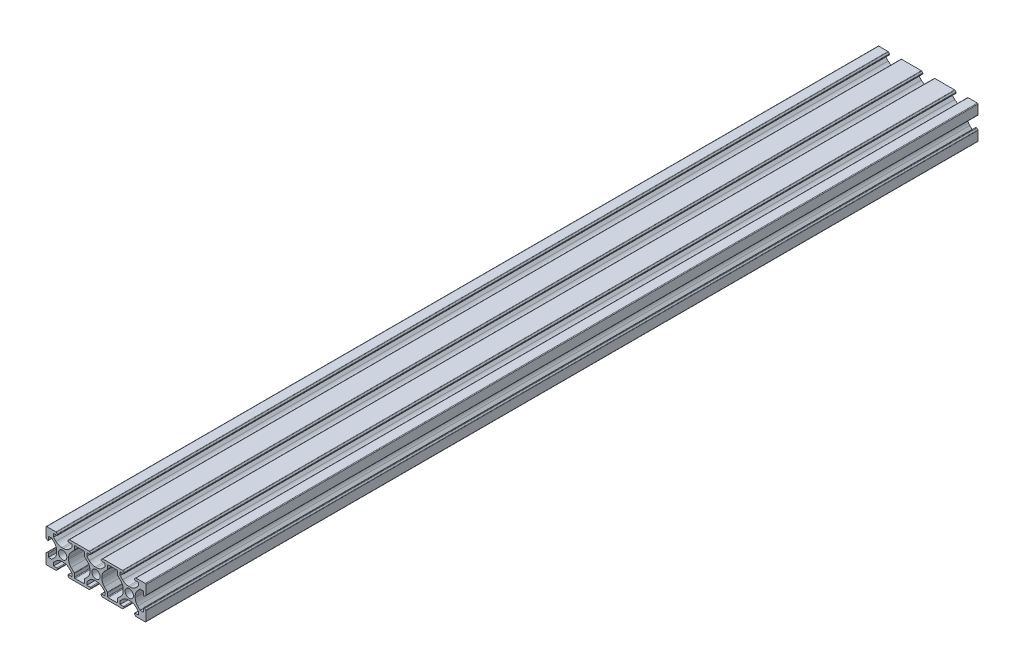
SolidWorks part; units mm, degrees
material "6063-O"
ref_plane "Plano frontal" through (0, 0, 0) normal (0, 0, 1) x (1, 0, 0)
ref_plane "Plano superior" through (0, 0, 0) normal (0, 1, 0) x (1, 0, 0)
ref_plane "Plano direito" through (0, 0, 0) normal (1, 0, 0) x (0, 0, -1)
sketch "Esboço1" plane through (0, 0, 0) normal (0, 0, 1) x (1, 0, 0)
  line L0 (-9.0343, 3.1) -> (-8.9, 3.1)
  line L3 (-10, 10) -> (-4.0657, 10)
  line L5 (-10, -10) -> (10, 10) construction
  line L6 (-10, 10) -> (10, -10) construction
  line L7 (-8.5, 3.5) -> (-8.5, 5.5)
  line L8 (-10, 0) -> (10, 0) construction
  line L9 (0, 10) -> (0, -10) construction
  line L12 (-8.5, 5.5) -> (-6.5607, 5.5)
  line L15 (-6.5607, 5.5) -> (-5.0645, 4.0038)
  line L16 (-3.6, 0.4683) -> (-3.6, 0)
  line L17 (-0.4683, 3.6) -> (0, 3.6)
  line L18 (-5.5, 6.5607) -> (-4.0038, 5.0645)
  line L21 (-5.5, 8.5) -> (-5.5, 6.5607)
  line L24 (-3.5, 8.5) -> (-5.5, 8.5)
  line L25 (-3.1, 9.0343) -> (-3.1, 8.9)
  line L44 (-10, 4.0657) -> (-10, 10)
  line L45 (-9.8828, 3.7828) -> (-9.3172, 3.2172)
  line L46 (-3.7828, 9.8828) -> (-3.2172, 9.3172)
  line L47 (-3.6, 0) -> (-2.5, 0)
  line L48 (0, 3.6) -> (0, 2.5)
  arc A0 (-3.5, 8.5) -> (-3.1, 8.9) centre (-3.5, 8.9) ccw
  arc A1 (-3.7828, 9.8828) -> (-4.0657, 10) centre (-4.0657, 9.6) ccw
  arc A2 (-10, 4.0657) -> (-9.8828, 3.7828) centre (-9.6, 4.0657) ccw
  arc A3 (-8.5, 3.5) -> (-8.9, 3.1) centre (-8.9, 3.5) cw
  arc A4 (-3.2172, 9.3172) -> (-3.1, 9.0343) centre (-3.5, 9.0343) cw
  arc A5 (-9.3172, 3.2172) -> (-9.0343, 3.1) centre (-9.0343, 3.5) ccw
  arc A6 (-3.6, 0.4683) -> (-5.0645, 4.0038) centre (-8.6, 0.4683) ccw
  arc A7 (-4.0038, 5.0645) -> (-0.4683, 3.6) centre (-0.4683, 8.6) ccw
  circle A8 centre (0, 0) radius 2.5
  point P6 (-10, 3.1)
  point P28 (-3.1, 8.5)
  point P31 (-3.1, 10)
  point P33 (-3.9, 10)
  point P36 (-10, 3.9)
  point P39 (-8.5, 3.1)
  point P42 (-3.1, 9.2)
  point P45 (-9.2, 3.1)
  point P48 (-3.6, 2.5393)
  point P51 (-2.5393, 3.6)
  dimension "D5" = 10
  dimension "D9" = 0.4
  dimension "D10" = 0.4
  dimension "D11" = 5
  dimension "D12" = 5
  dimension "D13" = 5
  dimension "D1" = 6.9
  dimension "D2" = 1.5
  dimension "D3" = 3.6
  dimension "D4" = 1.5
  dimension "D6" = 2.4
  dimension "D7" = 3.6
  dimension "D8" = 45
extrude "Ressalto-extrusão1" add sketch "Esboço1" along normal blind 500
sketch "Esboço3" plane through (0, 0, 0) normal (1, 0, 0) x (0, 0, -1)
  line L0 (0, 0) -> (-1000, 0) construction
  dimension "D1" = 1000
pattern_circular "PadrãoCircular1" count 4 over 360 about axis through (0, 0, 0) along (0, 0, 1) of "Ressalto-extrusão1"
pattern_linear "Padrão linear1" count 3 spacing 20 along (1, 0, 0) of "Ressalto-extrusão1", "PadrãoCircular1"
sketch "Esboço4" plane through (0, 0, 0) normal (0, 0, -1) x (-1, 0, 0)
  line L0 (-13.4393, 5.5) -> (-13, 5.9393)
  line L1 (-13, 8.5) -> (-13, 5.9393)
  line L2 (-10, 10) -> (-10, -10) construction
  line L3 (-4.0657, 10) -> (-15.9343, 10) construction
  line L4 (-15.9343, -10) -> (-4.0657, -10) construction
  line L5 (-11.5, 5.5) -> (-13.4393, 5.5) construction
  line L6 (-14.5, 8.5) -> (-14.5, 6.5607) construction
  line L7 (-7, 8.5) -> (-7, 5.9393)
  line L8 (-6.5607, 5.5) -> (-7, 5.9393)
  line L9 (-13, 8.5) -> (-7, 8.5)
  line L10 (-20, 0) -> (0, 0) construction
  line L11 (-13, -8.5) -> (-7, -8.5)
  line L12 (-6.5607, -5.5) -> (-7, -5.9393)
  line L13 (-7, -8.5) -> (-7, -5.9393)
  line L14 (-13, -8.5) -> (-13, -5.9393)
  line L15 (-13.4393, -5.5) -> (-13, -5.9393)
  line L16 (-13.4393, 5.5) -> (-13.4393, -5.5)
  line L17 (-6.5607, -5.5) -> (-6.5607, 5.5)
  line L31 (-40, 0) -> (-20, 0) construction
  line L32 (-33.4393, 5.5) -> (-33, 5.9393) [skipped]
  line L33 (-33, 8.5) -> (-33, 5.9393) [skipped]
  line L34 (-27, 8.5) -> (-27, 5.9393) [skipped]
  line L35 (-26.5607, 5.5) -> (-27, 5.9393) [skipped]
  line L36 (-33, 8.5) -> (-27, 8.5) [skipped]
  line L37 (-33, -8.5) -> (-27, -8.5) [skipped]
  line L38 (-26.5607, -5.5) -> (-27, -5.9393) [skipped]
  line L39 (-27, -8.5) -> (-27, -5.9393) [skipped]
  line L40 (-33, -8.5) -> (-33, -5.9393) [skipped]
  line L41 (-33.4393, -5.5) -> (-33, -5.9393) [skipped]
  line L42 (-33.4393, 5.5) -> (-33.4393, -5.5) [skipped]
  line L43 (-26.5607, -5.5) -> (-26.5607, 5.5) [skipped]
  line L44 (-30, 10) -> (-30, -10) construction
  dimension "D1" = 45
  dimension "D2" = 1.5
  dimension "D3" = 1.5
  dimension "D4" = 2
extrude "Corte-extrusão1" cut sketch "Esboço4" against normal through all
pattern_linear "Padrão linear2" count 2 spacing 20 along (1, 0, 0) of "Corte-extrusão1"
fillet "Filete1" radius 0.4 16 edges at (13, -5.9393, 250) (13, -8.5, 250) (7, -8.5, 250) (7, -5.9393, 250) (7, 8.5, 250) (7, 5.9393, 250) (13, 8.5, 250) (13, 5.9393, 250) (27, -8.5, 250) (27, -5.9393, 250) (27, 8.5, 250) (27, 5.9393, 250) (33, 8.5, 250) (33, -8.5, 250) (33, -5.9393, 250) (33, 5.9393, 250)
fillet "Filete2" radius 0.4 4 edges at (-10, 10, 250) (50, -10, 250) (50, 10, 250) (-10, -10, 250)
ref_plane "Plane1" through (20, 0, 0) normal (-1, 0, 0) x (0, 0, 1)
